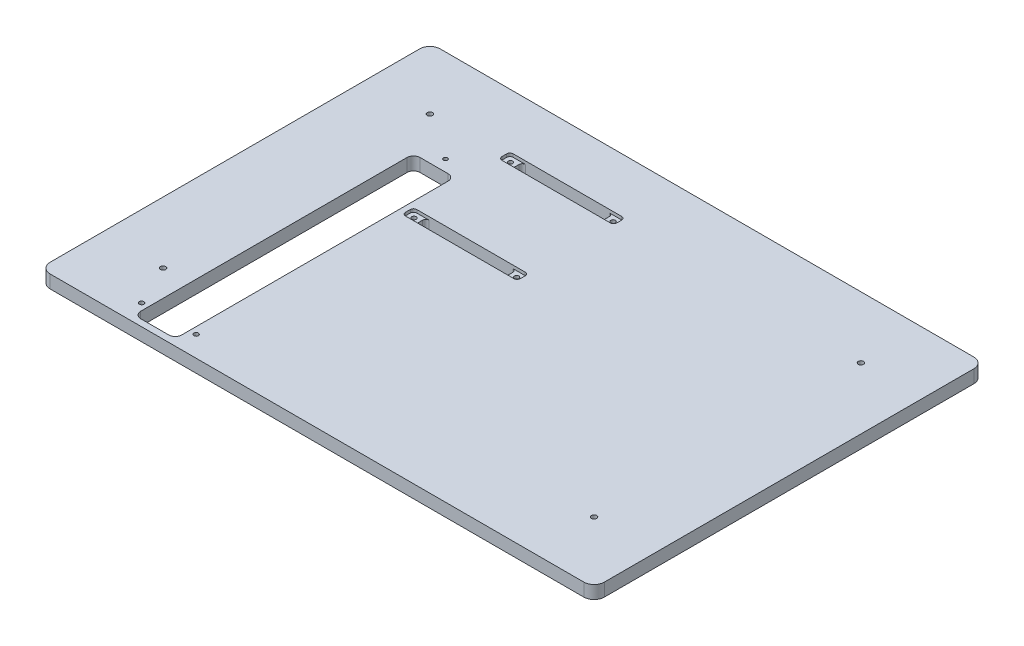
SolidWorks part; units mm, degrees
material "Acrylic (Medium-high impact)"
ref_plane "Front Plane" through (0, 0, 0) normal (0, 0, 1) x (1, 0, 0)
ref_plane "Top Plane" through (0, 0, 0) normal (0, 1, 0) x (1, 0, 0)
ref_plane "Right Plane" through (0, 0, 0) normal (1, 0, 0) x (0, 0, -1)
sketch "Sketch1" plane through (0, 0, 0) normal (0, 1, 0) x (1, 0, 0)
  line L1 (-260, 190) -> (260, 190)
  line L2 (-270, 180) -> (-270, -180)
  line L3 (-260, -190) -> (260, -190)
  line L4 (270, 180) -> (270, -180)
  line L5 (-270, 190) -> (270, -190) construction
  line L6 (-270, -190) -> (270, 190) construction
  arc A0 (270, 180) -> (260, 190) centre (260, 180) ccw
  arc A1 (270, -180) -> (260, -190) centre (260, -180) cw
  arc A2 (-260, 190) -> (-270, 180) centre (-260, 180) ccw
  arc A3 (-270, -180) -> (-260, -190) centre (-260, -180) ccw
  circle A4 centre (-210, 130) radius 39.6875 construction
  circle A5 centre (-210, -130) radius 39.6875 construction
  circle A6 centre (210, -130) radius 39.6875 construction
  circle A7 centre (210, 130) radius 39.6875 construction
  point P0 (0, 0)
  dimension "D3" = 10
  dimension "D4" = 79.375
  dimension "D1" = 540
  dimension "D2" = 380
  dimension "D5" = 60
  dimension "D6" = 60
  dimension "D7" = 60
  dimension "D8" = 60
  dimension "D9" = 60
  dimension "D10" = 60
  dimension "D11" = 60
  dimension "D12" = 60
extrude "Boss-Extrude1" add sketch "Sketch1" against normal blind 12.7
hole_wizard "Tap Drill for 1/4-20 Tap1" positions "Sketch8" profile "Sketch9" hole size "1/4-20" standard "ANSI Inch" end condition through all
sketch "Sketch8" plane through (0, 0, 0) normal (0, 1, 0) x (1, 0, 0)
  point P0 (-210, 130)
  point P3 (-210, -130)
  point P6 (210, 130)
  point P9 (210, -130)
sketch "Sketch9" plane through (-210, 0, -130) normal (1, 0, 0) x (0, 0, 1)
  line L0 (0, 0) -> (0, 12.7)
  line L1 (0, 12.7) -> (2.5527, 12.7)
  line L2 (2.5527, 12.7) -> (2.5527, 0)
  line L5 (2.5527, 0) -> (0, 0)
  line L11 (0, -6.35) -> (0, 107.95) construction
  dimension "Thru Hole Dia." = 5.1054
  dimension "Thru Hole Depth" = 12.7
sketch "Sketch10" plane through (0, 0, 0) normal (0, 1, 0) x (1, 0, 0)
  line L0 (260, 190) -> (-260, 190) construction
  line L1 (-270, 180) -> (-270, -180) construction
  line L2 (-260, -190) -> (260, -190) construction
  circle A8 centre (-137.95, -169.8549) radius 2.25
  circle A9 centre (-191.05, -169.8549) radius 2.25
  circle A10 centre (-133, 131.5229) radius 2.2
  circle A11 centre (-33, 131.5229) radius 2.2
  circle A12 centre (-133, 37.5229) radius 2.2
  circle A13 centre (-33, 37.5229) radius 2.2
  dimension "D2" = 100
  dimension "D4" = 4.4
  dimension "D5" = 94
  dimension "D6" = 4.5
  dimension "D1" = 58.4771
  dimension "D3" = 137
  dimension "D7" = 53.1
  dimension "D8" = 78.95
  dimension "D9" = 20.1451
extrude "Cut-Extrude1" cut sketch "Sketch10" against normal through all
sketch "Sketch11" plane through (0, 0, 0) normal (0, 1, 0) x (1, 0, 0)
  line L1 (-39, 32.0229) -> (-127, 32.0229)
  line L2 (-39, 32.0229) -> (-39, 43.0229)
  line L3 (-39, 43.0229) -> (-127, 43.0229)
  line L4 (-127, 32.0229) -> (-127, 43.0229)
  line L5 (-39, 32.0229) -> (-127, 43.0229) construction
  line L6 (-39, 43.0229) -> (-127, 32.0229) construction
  line L8 (-133, 37.5229) -> (-33, 37.5229) construction
  line L11 (-133, 131.5229) -> (-33, 131.5229) construction
  line L15 (-127, 126.0229) -> (-39, 126.0229)
  line L16 (-127, 126.0229) -> (-127, 137.0229)
  line L17 (-127, 137.0229) -> (-39, 137.0229)
  line L18 (-39, 126.0229) -> (-39, 137.0229)
  line L19 (-127, 126.0229) -> (-39, 137.0229) construction
  line L20 (-127, 137.0229) -> (-39, 126.0229) construction
  point P0 (-83, 37.5229)
  point P21 (-83, 37.5229)
  point P22 (-83, 131.5229)
  point P26 (-83, 131.5229)
  dimension "D1" = 88
  dimension "D2" = 11
extrude "Cut-Extrude2" cut sketch "Sketch11" against normal up to next
sketch "Sketch12" plane through (0, 0, 0) normal (0, 1, 0) x (1, 0, 0)
  line L1 (-260, -190) -> (260, -190) construction
  line L2 (-164.5, 88.5401) -> (-164.5, -183.6799) construction
  line L3 (-270, 180) -> (-270, -180) construction
  line L4 (-184.5, -183.6799) -> (-144.5, -183.6799)
  line L5 (-184.5, -183.6799) -> (-184.5, 88.5401)
  line L6 (-184.5, 88.5401) -> (-144.5, 88.5401)
  line L7 (-144.5, -183.6799) -> (-144.5, 88.5401)
  dimension "D1" = 40
  dimension "D2" = 272.22
  dimension "D3" = 6.3201
  dimension "D4" = 105.5
extrude "Cut-Extrude3" cut sketch "Sketch12" against normal through all
sketch "Sketch13" plane through (0, 0, 0) normal (0, 1, 0) x (1, 0, 0)
  line L0 (-39, 32.0229) -> (-39, 43.0229) construction
  line L1 (-27, 32.0229) -> (-39, 32.0229)
  line L2 (-27, 32.0229) -> (-27, 43.0229)
  line L3 (-27, 43.0229) -> (-39, 43.0229)
  line L4 (-39, 32.0229) -> (-39, 43.0229)
  line L5 (-27, 32.0229) -> (-39, 43.0229) construction
  line L6 (-27, 43.0229) -> (-39, 32.0229) construction
  line L7 (-39, 126.0229) -> (-39, 137.0229) construction
  line L8 (-27, 126.0229) -> (-39, 126.0229)
  line L9 (-27, 126.0229) -> (-27, 137.0229)
  line L10 (-27, 137.0229) -> (-39, 137.0229)
  line L11 (-39, 126.0229) -> (-39, 137.0229)
  line L12 (-27, 126.0229) -> (-39, 137.0229) construction
  line L13 (-27, 137.0229) -> (-39, 126.0229) construction
  line L14 (-127, 43.0229) -> (-127, 32.0229) construction
  line L15 (-139, 32.0229) -> (-127, 32.0229)
  line L16 (-139, 32.0229) -> (-139, 43.0229)
  line L17 (-139, 43.0229) -> (-127, 43.0229)
  line L18 (-127, 32.0229) -> (-127, 43.0229)
  line L19 (-139, 32.0229) -> (-127, 43.0229) construction
  line L20 (-139, 43.0229) -> (-127, 32.0229) construction
  line L21 (-127, 137.0229) -> (-127, 126.0229) construction
  line L22 (-139, 126.0229) -> (-127, 126.0229)
  line L23 (-139, 126.0229) -> (-139, 137.0229)
  line L24 (-139, 137.0229) -> (-127, 137.0229)
  line L25 (-127, 126.0229) -> (-127, 137.0229)
  line L26 (-139, 126.0229) -> (-127, 137.0229) construction
  line L27 (-139, 137.0229) -> (-127, 126.0229) construction
  circle A0 centre (-33, 37.5229) radius 2.2 construction
  circle A1 centre (-33, 37.5229) radius 2.2 construction
  circle A2 centre (-133, 131.5229) radius 2.2 construction
  circle A3 centre (-133, 37.5229) radius 2.2 construction
  circle A4 centre (-33, 131.5229) radius 2.2 construction
  circle A5 centre (-133, 131.5229) radius 2.2 construction
  circle A6 centre (-133, 37.5229) radius 2.2 construction
  circle A7 centre (-33, 131.5229) radius 2.2 construction
  dimension "D1" = 11
  dimension "D2" = 11
  dimension "D3" = 11
  dimension "D4" = 11
extrude "Cut-Extrude4" cut sketch "Sketch13" against normal blind 3
fillet "Fillet2" radius 6.35 4 edges at (-144.5, -6.35, -88.5401) (-184.5, -6.35, -88.5401) (-144.5, -6.35, 183.6799) (-184.5, -6.35, 183.6799)
fillet "Fillet3" radius 3.175 16 edges at (-127, -7.85, -137.0229) (-127, -7.85, -126.0229) (-139, -1.5, -137.0229) (-139, -1.5, -126.0229) (-39, -7.85, -126.0229) (-39, -7.85, -137.0229) (-27, -1.5, -126.0229) (-27, -1.5, -137.0229) (-27, -1.5, -32.0229) (-27, -1.5, -43.0229) (-39, -7.85, -43.0229) (-39, -7.85, -32.0229) (-127, -7.85, -43.0229) (-127, -7.85, -32.0229) (-139, -1.5, -43.0229) (-139, -1.5, -32.0229)
sketch "Sketch14" plane through (0, 0, 0) normal (0, 1, 0) x (1, 0, 0)
  line L0 (-270, 180) -> (-270, -180) construction
  line L1 (260, 190) -> (-260, 190) construction
  circle A0 centre (-164.5, 99.7151) radius 2
  dimension "D1" = 4
  dimension "D2" = 105.5
  dimension "D3" = 90.2849
extrude "Cut-Extrude5" cut sketch "Sketch14" against normal through all
